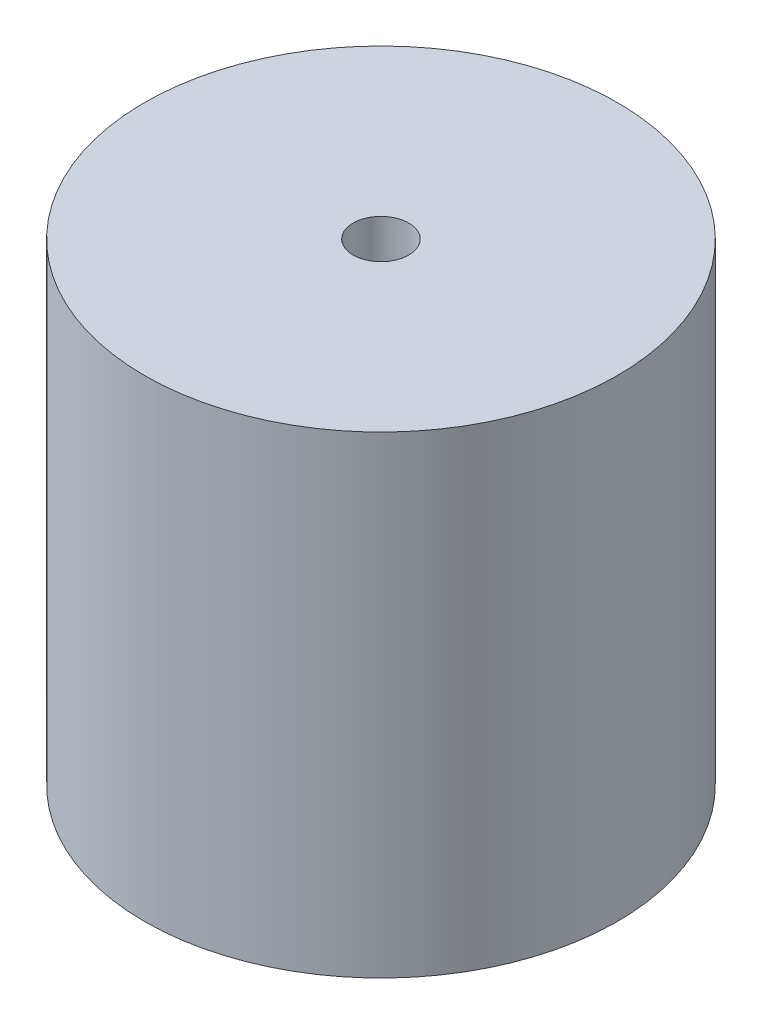
SolidWorks part; units mm, degrees
ref_plane "Front Plane" through (0, 0, 0) normal (0, 0, 1) x (1, 0, 0)
ref_plane "Top Plane" through (0, 0, 0) normal (0, 1, 0) x (1, 0, 0)
ref_plane "Right Plane" through (0, 0, 0) normal (1, 0, 0) x (0, 0, -1)
sketch "Sketch1" plane through (0, 0, 0) normal (0, 1, 0) x (1, 0, 0)
  circle A0 centre (0, 0) radius 10
  dimension "D1" = 20
extrude "Boss-Extrude1" add sketch "Sketch1" along normal blind 20
sketch "Sketch2" plane through (0, 20, 0) normal (0, 1, 0) x (1, 0, 0)
  circle A0 centre (0, 0) radius 1.175
  dimension "D1" = 2.35
extrude "Cut-Extrude1" cut sketch "Sketch2" against normal blind 20
sketch "Sketch3" plane through (0, 0, 0) normal (0, -1, 0) x (-1, 0, 0)
  circle A0 centre (0, 0) radius 2.45
  dimension "D1" = 4.9
extrude "Cut-Extrude2" cut sketch "Sketch3" against normal blind 15
